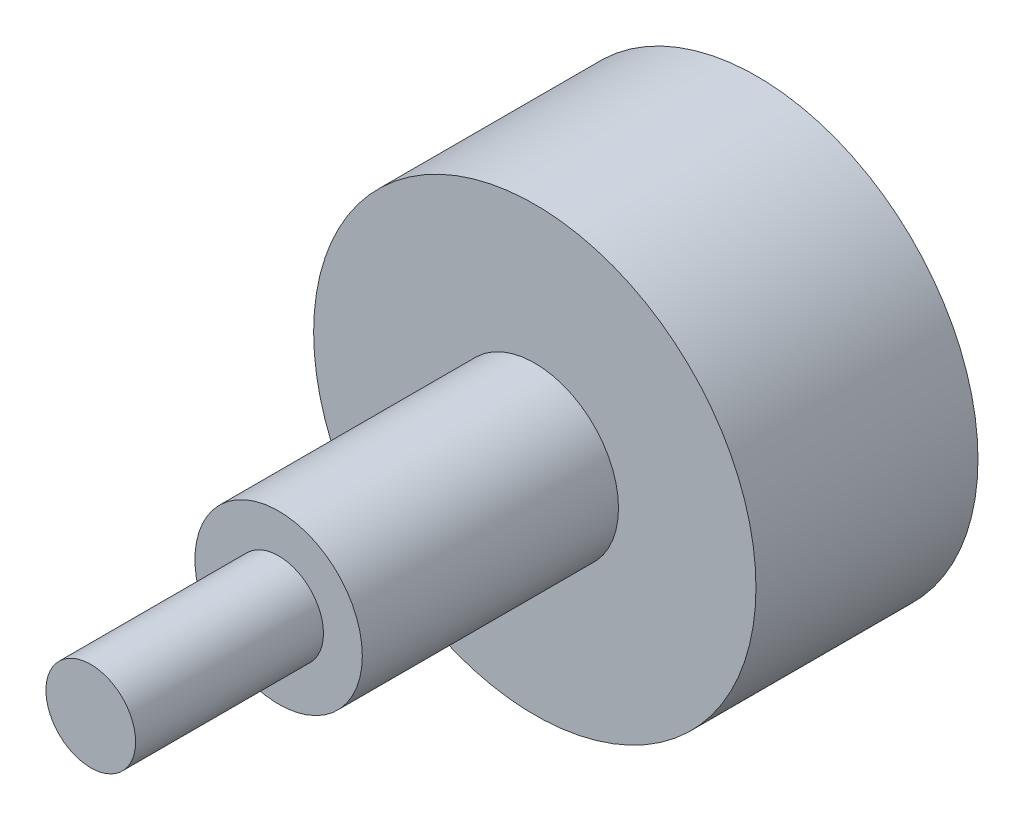
SolidWorks part; units mm, degrees
ref_plane "Front Plane" through (0, 0, 0) normal (0, 0, 1) x (1, 0, 0)
ref_plane "Top Plane" through (0, 0, 0) normal (0, 1, 0) x (1, 0, 0)
ref_plane "Right Plane" through (0, 0, 0) normal (1, 0, 0) x (0, 0, -1)
sketch "Sketch2" plane through (0, 0, 0) normal (0, 0, 1) x (1, 0, 0)
  circle A0 centre (0, 0) radius 12.5
  dimension "D1" = 25
extrude "Boss-Extrude1" add sketch "Sketch2" along normal blind 13
sketch "Sketch3" plane through (0, 0, 13) normal (0, 0, 1) x (1, 0, 0)
  circle A0 centre (0, 0) radius 2.45
  dimension "D1" = 4.9
extrude "Boss-Extrude2" add sketch "Sketch3" along normal blind 26
sketch "Sketch4" plane through (0, 0, 0) normal (0, 0, -1) x (-1, 0, 0)
  circle A0 centre (0, 0) radius 12.9
  dimension "D1" = 25.8
extrude "Boss-Extrude3" add sketch "Sketch4" against normal up to surface (13 mm away) up to face at (2.45, 0, 13)
sketch "Sketch5" plane through (0, 0, 39) normal (0, 0, 1) x (1, 0, 0)
  circle A0 centre (0, 0) radius 2.625
  dimension "D1" = 5.25
extrude "Boss-Extrude4" add sketch "Sketch5" against normal up to surface (26 mm away) up to face at (2.45, 0, 13)
sketch "Sketch6" plane through (0, 0, 13) normal (0, 0, 1) x (1, 0, 0)
  circle A0 centre (0, 0) radius 4.9
  dimension "D1" = 9.8
extrude "Boss-Extrude5" add sketch "Sketch6" along normal blind 15
sketch "Sketch7" plane through (0, 0, 0) normal (0, 0, -1) x (-1, 0, 0)
  circle A0 centre (0, 0) radius 13.125
  dimension "D1" = 26.25
extrude "Boss-Extrude6" add sketch "Sketch7" against normal up to surface (13 mm away) up to face at (4.9, 0, 13)
sketch "Sketch8" plane through (0, 0, 0) normal (0, 0, -1) x (-1, 0, 0)
  circle A0 centre (0, 0) radius 12.95
  circle A1 centre (0, 0) radius 13.125
  dimension "D1" = 25.9
extrude "Cut-Extrude1" cut sketch "Sketch8" against normal through all
